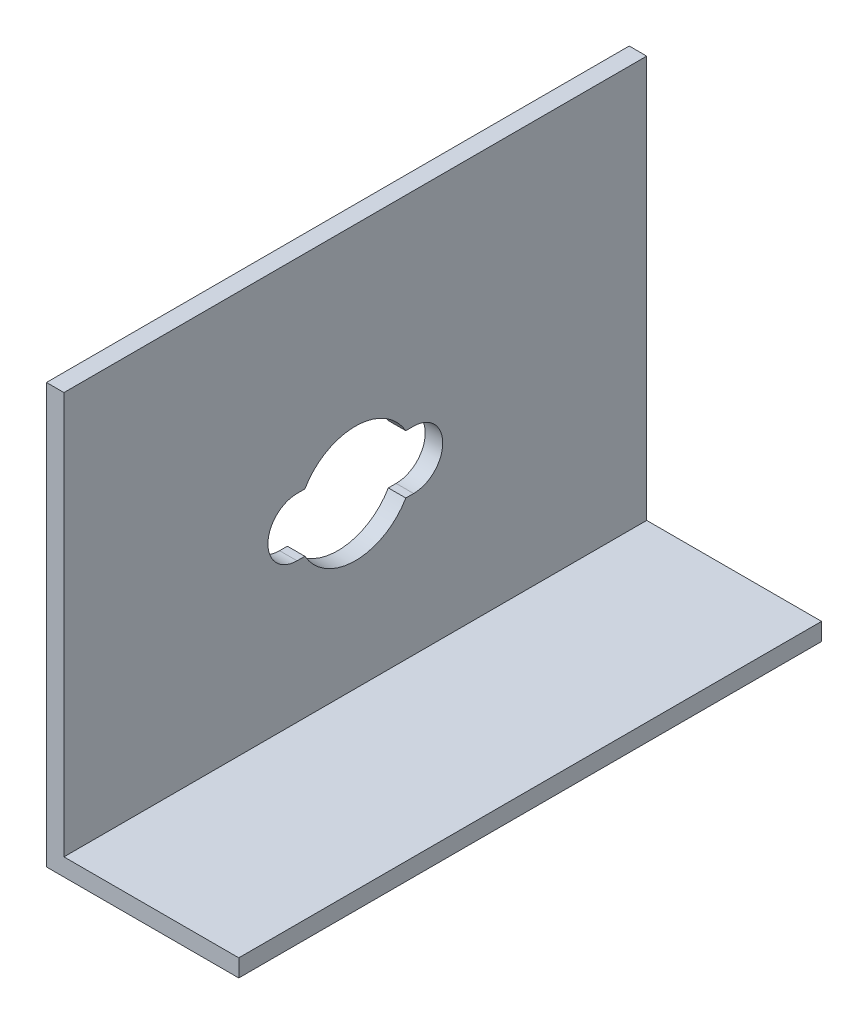
SolidWorks part; units mm, degrees
ref_plane "Front Plane" through (0, 0, 0) normal (0, 0, 1) x (1, 0, 0)
ref_plane "Top Plane" through (0, 0, 0) normal (0, 1, 0) x (1, 0, 0)
ref_plane "Right Plane" through (0, 0, 0) normal (1, 0, 0) x (0, 0, -1)
sketch "Sketch1" plane through (0, 0, 0) normal (0, 0, 1) x (1, 0, 0)
  line L0 (0, 72) -> (3, 72)
  line L1 (3, 3) -> (3, 72)
  line L2 (0, 72) -> (0, 0)
  line L3 (0, 0) -> (33, 0)
  line L4 (33, 0) -> (33, 3)
  line L5 (33, 3) -> (3, 3)
  dimension "D1" = 30
  dimension "D2" = 3
  dimension "D3" = 3
  dimension "D4" = 72
extrude "Boss-Extrude1" add sketch "Sketch1" along normal blind 100
sketch "Sketch2" plane through (0, 0, 0) normal (-1, 0, 0) x (0, 0, 1)
  line L0 (58.6603, 37) -> (60, 37)
  line L1 (40, 32) -> (60, 32) construction
  line L2 (40, 37) -> (41.3397, 37)
  line L3 (40, 27) -> (41.3397, 27)
  line L4 (58.6603, 27) -> (60, 27)
  line L5 (100, 0) -> (0, 0) construction
  line L7 (0, 72) -> (0, 0) construction
  arc A0 (40, 37) -> (40, 27) centre (40, 32) ccw
  arc A1 (60, 27) -> (60, 37) centre (60, 32) ccw
  arc A2 (58.6603, 37) -> (41.3397, 37) centre (50, 32) ccw
  arc A3 (41.3397, 27) -> (58.6603, 27) centre (50, 32) ccw
  point P2 (50, 32)
  dimension "D1" = 5
  dimension "D3" = 20
  dimension "D6" = 5
  dimension "D2" = 20
  dimension "D4" = 5
  dimension "D5" = 5
  dimension "D7" = 10
  dimension "D8" = 10
  dimension "D9" = 1.3397
  dimension "D10" = 1.3397
  dimension "D11" = 32
  dimension "D12" = 50
extrude "Cut-Extrude1" cut sketch "Sketch2" against normal blind 100
